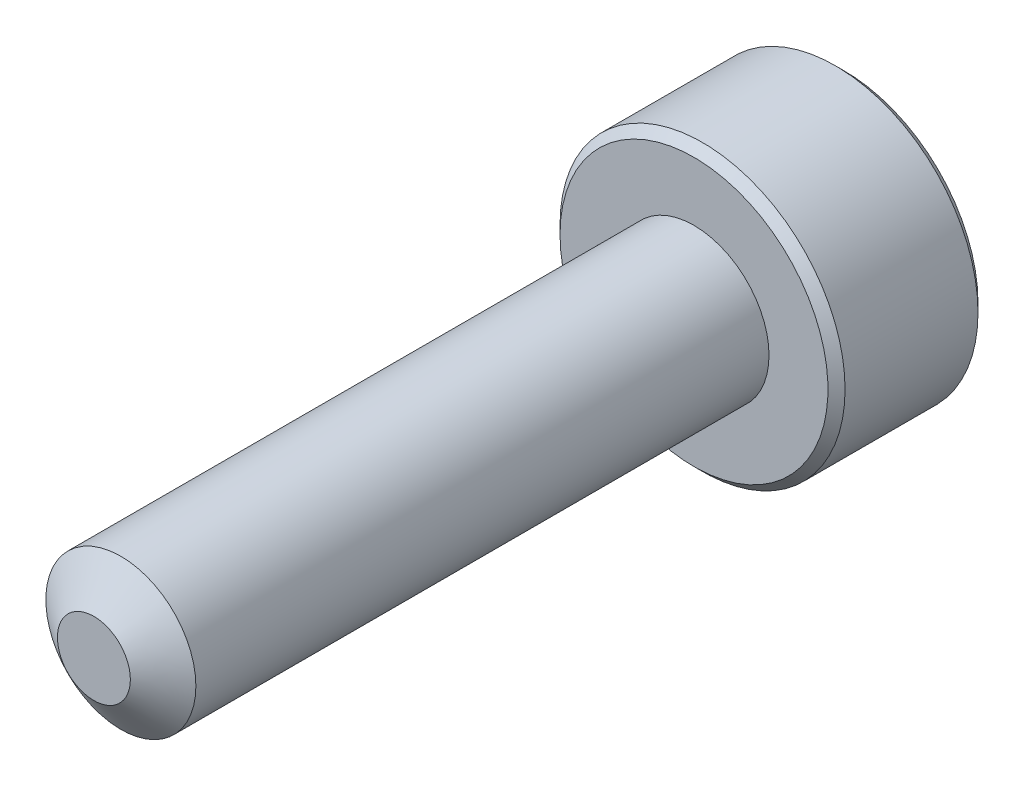
SolidWorks part; units mm, degrees
ref_plane "Front Plane" through (0, 0, 0) normal (0, 0, 1) x (1, 0, 0)
ref_plane "Top Plane" through (0, 0, 0) normal (0, 1, 0) x (1, 0, 0)
ref_plane "Right Plane" through (0, 0, 0) normal (1, 0, 0) x (0, 0, -1)
sketch "Sketch1" plane through (0, 0, 0) normal (0, 0, 1) x (1, 0, 0)
  circle A0 centre (0, 0) radius 1
  dimension "OD" = 2
extrude "Extrude1" add sketch "Sketch1" against normal blind 8
cosmetic thread "Cosmetic Thread1" parameters "D1"=21.6402, "D2"=1.548
sketch "Sketch2" plane through (0, 0, 0) normal (0, 0, 1) x (1, 0, 0)
  circle A0 centre (0, 0) radius 1 construction
  circle A1 centre (0, 0) radius 1
sketch "Sketch3" plane through (0, 0, 0) normal (1, 0, 0) x (0, 0, -1)
  line L0 (-0.35, 1) -> (-0.2, 0.7402)
  line L1 (-0.2, 0.7402) -> (-0.15, 0.7402)
  line L2 (-0.15, 0.7402) -> (0, 1)
  line L3 (-0.35, 1) -> (0, 1)
  line L4 (-0.175, 1) -> (-0.175, 0.7402) construction
  line L5 (-0.275, 0.8701) -> (-0.075, 0.8701) construction
  line L6 (0, 1) -> (0, -1) construction
  line L7 (0, -1) -> (8, -1) construction
  point P11 (1.8, -1)
  dimension "D1" = 0.05
  dimension "D2" = 0.2
  dimension "D3" = 60
  dimension "D4" = 1.8
sketch "Sketch4" plane through (0, 0, 0) normal (1, 0, 0) x (0, 0, -1)
  line L0 (0.3598, 1) -> (0, 0.4862)
  line L1 (0, 0.4862) -> (0, 1)
  line L2 (0.3598, 1) -> (0, 1)
  line L3 (-0.35, 1) -> (0, 1) construction
  line L4 (0, 0) -> (7.0209, 0) construction
  dimension "D1" = 55
  dimension "D2" = 0.254
revolve "Cut-Revolve1" cut sketch "Sketch4" angle 360 about L4
sketch "Sketch6" plane through (0, 0, -8) normal (0, 0, -1) x (-1, 0, 0)
  circle A0 centre (0, 0) radius 1.9
  dimension "head dia" = 3.8
extrude "Extrude2" add sketch "Sketch6" along normal blind 2
sketch "Sketch7" plane through (0, 0, -10) normal (0, 0, -1) x (-1, 0, 0)
  line L1 (0, 0.866) -> (-0.75, 0.433)
  line L2 (-0.75, 0.433) -> (-0.75, -0.433)
  line L3 (-0.75, -0.433) -> (0, -0.866)
  line L4 (0, -0.866) -> (0.75, -0.433)
  line L5 (0.75, -0.433) -> (0.75, 0.433)
  line L6 (0.75, 0.433) -> (0, 0.866)
  circle A0 centre (0, 0) radius 0.75 construction
  dimension "hex dia" = 1.5
extrude "Cut-Extrude1" cut sketch "Sketch7" against normal blind 1.125
sketch "Sketch8" plane through (0, 0, -10) normal (0, 0, -1) x (-1, 0, 0)
  circle A0 centre (0, 0) radius 0.866
extrude "Cut-Extrude2" cut sketch "Sketch8" against normal through all draft 45
chamfer "Chamfer1" distance 0.114 angle 45 2 edges at (-1.9, 0, -10) (-1.9, 0, -8)
sketch "Sketch9" plane through (0, 0, 0) normal (1, 0, 0) x (0, 0, -1)
  line L0 (0, 1) -> (0, -1) construction
  line L1 (2.2, 1) -> (2.2, -1) construction
  dimension "D1" = 2.2
sketch "Sketch10" plane through (0, 0, 0) normal (1, 0, 0) x (0, 0, -1)
  line L0 (8, 1) -> (8, 0)
  line L1 (8, 1) -> (7.9, 1)
  line L2 (7.9, 1) -> (7.4858, 0)
  line L3 (8, 0) -> (7.4858, 0)
  line L4 (8, 1.786) -> (8, -1.786) construction
  dimension "D1" = 22.5
  dimension "D2" = 0.1
revolve "Revolve1" add sketch "Sketch10" angle 360 about L3
